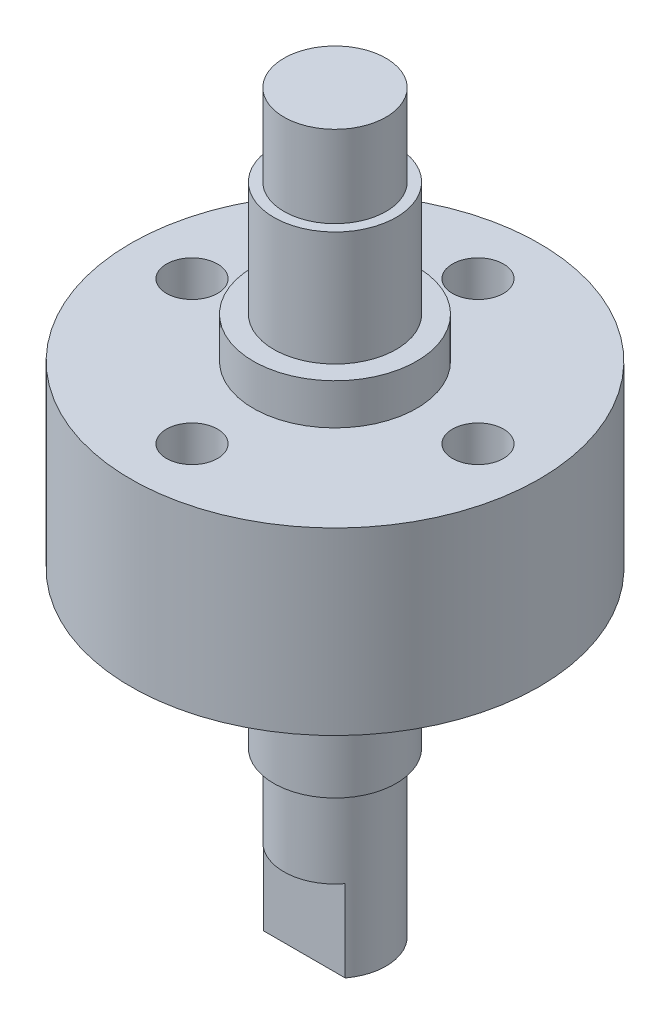
SolidWorks part; units mm, degrees
ref_plane "前视基准面" through (0, 0, 0) normal (0, 0, 1) x (1, 0, 0)
ref_plane "上视基准面" through (0, 0, 0) normal (0, 1, 0) x (1, 0, 0)
ref_plane "右视基准面" through (0, 0, 0) normal (1, 0, 0) x (0, 0, -1)
sketch "Model" plane through (0, 0, 0) normal (0, 0, 1) x (1, 0, 0)
  line L0 (-1.7864, 30.378) -> (-1.7864, -5.622)
  line L1 (8.2136, 9.978) -> (8.2136, 18.778)
  line L3 (2.2136, 18.778) -> (2.2136, 20.778)
  line L5 (2.2136, 7.978) -> (2.2136, 9.978)
  line L7 (1.2136, 2.378) -> (1.2136, 7.978)
  line L9 (1.2136, 20.778) -> (1.2136, 26.378)
  line L11 (0.7136, -5.622) -> (0.7136, 2.378)
  line L13 (0.7136, 26.378) -> (0.7136, 30.378)
  line L16 (1.2136, 20.778) -> (2.2136, 20.778)
  line L20 (-1.7864, -5.622) -> (0.7136, -5.622)
  line L21 (-1.7864, 30.378) -> (0.7136, 30.378)
  line L22 (-1.7864, 30.378) -> (-1.7864, -5.622) construction
  line L23 (0.7136, 26.378) -> (1.2136, 26.378)
  line L24 (2.2136, 18.778) -> (8.2136, 18.778)
  line L25 (2.2136, 9.978) -> (8.2136, 9.978)
  line L26 (1.2136, 7.978) -> (2.2136, 7.978)
  line L27 (0.7136, 2.378) -> (1.2136, 2.378)
  dimension "D1" = 4
  dimension "D2" = 5.6
  dimension "D3" = 2
  dimension "D4" = 8.8
  dimension "D5" = 2
  dimension "D6" = 5.6
  dimension "D7" = 8
  dimension "D8" = 2.5
  dimension "D9" = 3
  dimension "D10" = 4
  dimension "D11" = 10
  dimension "D12" = 4
  dimension "D13" = 3
  dimension "D14" = 2.5
revolve "旋转1" add sketch "Model" angle 360 about L22
sketch "草图2" plane through (0, 9.978, 0) normal (0, -1, 0) x (1, 0, 0)
  circle A0 centre (-1.7864, 0) radius 7 construction
  circle A1 centre (-1.7864, 7) radius 1.5
  dimension "D1" = 14
  dimension "D2" = 3
hole_wizard "M3 螺纹孔1" positions "3D草图1" profile "草图4" tap size "M3" standard "GB" end condition through all
sketch3d "3D草图1"
  point P0 (-1.7864, 9.978, 7)
sketch "草图4" plane through (-1.7864, 9.978, 7) normal (1, 0, 0) x (0, 0, -1)
  line L0 (0, 0) -> (0, 20.4)
  line L1 (0, 20.4) -> (1.25, 20.4)
  line L2 (1.25, 20.4) -> (1.25, 0)
  line L5 (1.25, 0) -> (0, 0)
  line L11 (0, -6.35) -> (0, 107.95) construction
  dimension "通孔螺纹孔钻头直径" = 2.5
  dimension "通孔螺纹孔钻头深度" = 20.4
cosmetic thread "孔螺蚊线1" parameters "D2"=3
pattern_circular "阵列(圆周)1" count 4 over 360 about axis through (-1.7864, 0, 0) along (0, 1, 0) of "M3 螺纹孔1"
sketch "草图5" plane through (0, -5.622, 0) normal (0, -1, 0) x (1, 0, 0)
  line L0 (-3.7864, 1.5) -> (0.2136, 1.5)
  line L1 (0.2136, 1.5) -> (0.2136, 5.3333)
  line L2 (0.2136, 5.3333) -> (-4.133, 4.4308)
  line L3 (-4.133, 4.4308) -> (-3.7864, 1.5)
  circle A0 centre (-1.7864, 0) radius 2.5 construction
  dimension "D1" = 1.5
extrude "切除-拉伸1" cut sketch "草图5" against normal blind 4
